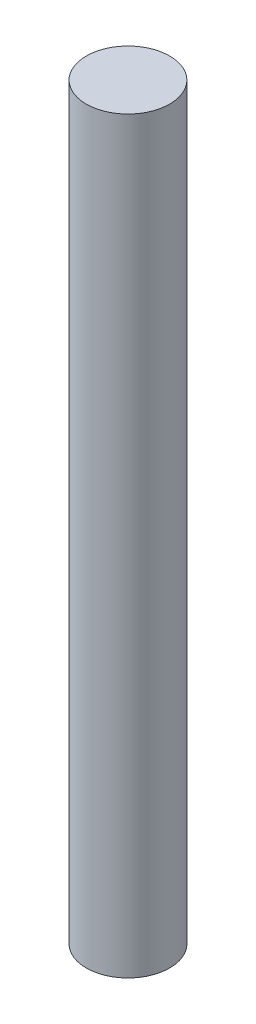
SolidWorks part; units mm, degrees
ref_plane "Front Plane" through (0, 0, 0) normal (0, 0, 1) x (1, 0, 0)
ref_plane "Top Plane" through (0, 0, 0) normal (0, 1, 0) x (1, 0, 0)
ref_plane "Right Plane" through (0, 0, 0) normal (1, 0, 0) x (0, 0, -1)
sketch "Sketch2" plane through (0, 0, 0) normal (0, 1, 0) x (1, 0, 0)
  circle A0 centre (0, 0) radius 3.9
  dimension "D1" = 7.8
extrude "Boss-Extrude1" add sketch "Sketch2" along normal blind 70
